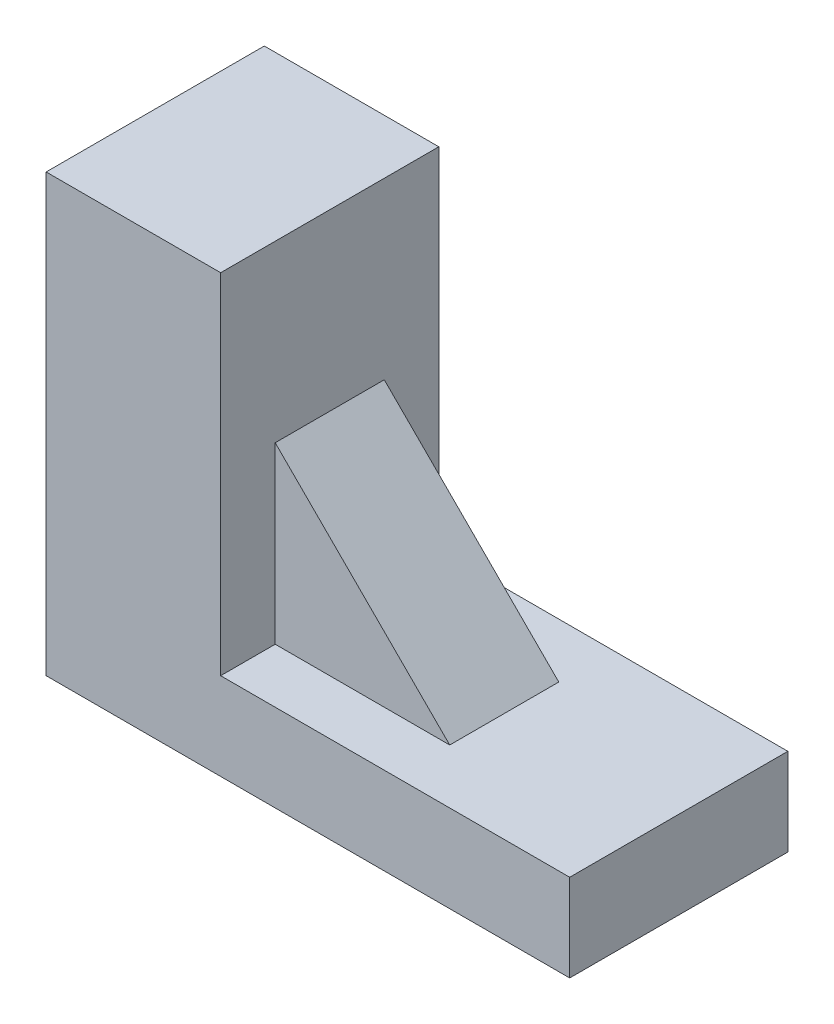
SolidWorks part; units mm, degrees
ref_plane "前视基准面" through (0, 0, 0) normal (0, 0, 1) x (1, 0, 0)
ref_plane "上视基准面" through (0, 0, 0) normal (0, 1, 0) x (1, 0, 0)
ref_plane "右视基准面" through (0, 0, 0) normal (1, 0, 0) x (0, 0, -1)
other "Configuration Table"
sketch "草图4" plane through (0, 0, 0) normal (0, 0, 1) x (1, 0, 0)
  line L0 (0, 0) -> (0, -20)
  line L1 (0, -20) -> (24, -20)
  line L2 (24, -20) -> (24, -16)
  line L3 (24, -16) -> (8, -16)
  line L4 (8, -16) -> (8, 0)
  line L5 (8, 0) -> (0, 0)
  dimension "D1" = 24
  dimension "D2" = 20
  dimension "D3" = 8
  dimension "D4" = 4
extrude "凸台-拉伸1" add sketch "草图4" against normal blind 10
ref_plane "基准面5" through (0, 0, -5) normal (0, 0, 1) x (1, 0, 0)
sketch "草图20" plane through (0, 0, -5) normal (0, 0, 1) x (1, 0, 0)
  line L0 (8, -8) -> (16, -16)
  line L1 (8, -16) -> (8, 0) construction
  line L2 (24, -16) -> (8, -16) construction
rib "筋29" sketch "草图20" sketch "草图20" thickness 5 extrusion direction parallel to sketch draft on no parameters "D1"=5
